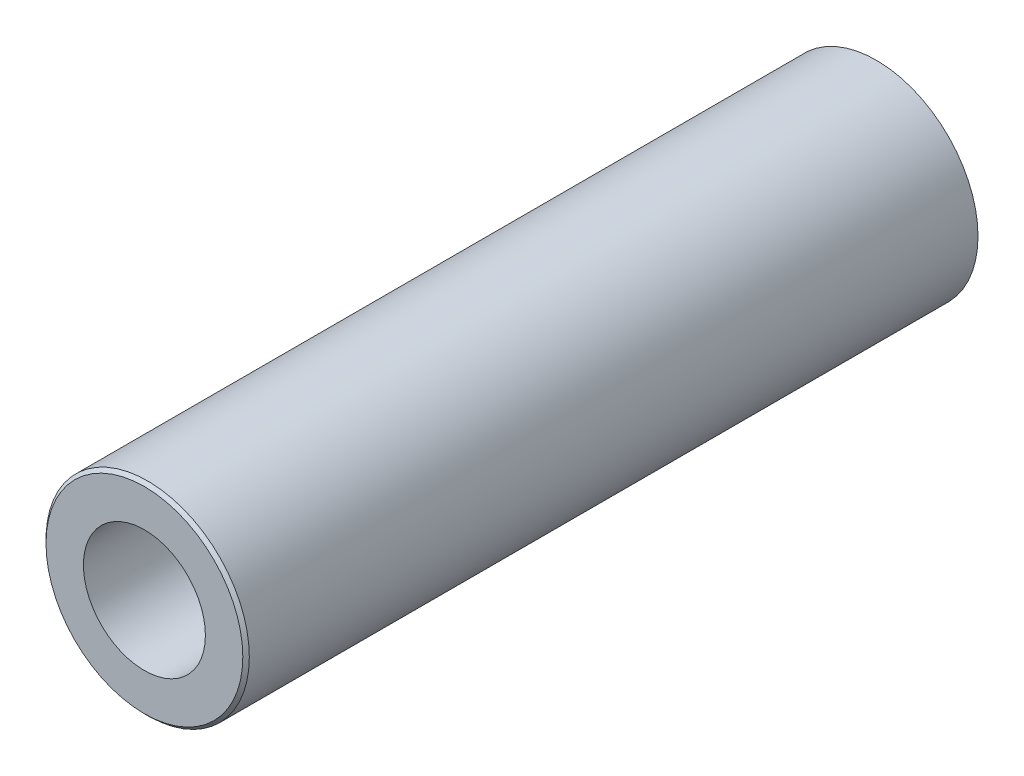
SolidWorks part; units mm, degrees
material "AISI 4130 Steel, annealed at 865C"
ref_plane "Front" through (0, 0, 0) normal (0, 0, 1) x (1, 0, 0)
ref_plane "Top" through (0, 0, 0) normal (0, 1, 0) x (1, 0, 0)
ref_plane "Right" through (0, 0, 0) normal (1, 0, 0) x (0, 0, -1)
sketch "Sketch1" plane through (0, 0, 0) normal (0, 0, 1) x (1, 0, 0)
  circle A0 centre (0, 0) radius 7.9375
  dimension "D1" = 15.875
extrude "Boss-Extrude1" add sketch "Sketch1" along normal blind 57.15
chamfer "Chamfer1" distance 0.254 angle 45 1 edges at (7.9375, 0, 57.15)
sketch "Sketch2" plane through (0, 0, 0) normal (0, 0, -1) x (-1, 0, 0)
  circle A0 centre (0, 0) radius 6.4643
  circle A1 centre (0, 0) radius 7.9375 construction
  dimension "D1" = 1.4732
sketch "Sketch4" [suppressed] plane through (0, 0, 19.05) normal (0, 0, 1) x (1, 0, 0)
  line L1 (6.4158, 0) -> (3.2079, 5.5563)
  line L2 (3.2079, 5.5563) -> (-3.2079, 5.5563)
  line L3 (-3.2079, 5.5563) -> (-6.4158, 0)
  line L4 (-6.4158, 0) -> (-3.2079, -5.5563)
  line L5 (-3.2079, -5.5563) -> (3.2079, -5.5563)
  line L6 (3.2079, -5.5563) -> (6.4158, 0)
  circle A0 centre (0, 0) radius 5.5562 construction
  circle A1 centre (0, 0) radius 6.35 construction
  circle A2 centre (0, 0) radius 6.35
  dimension "D1" = 11.1125
extrude "Cut-Extrude3" [suppressed] cut sketch "Sketch4" against normal blind 5.5562
hole_wizard "Tap Drill for 3/8-24 Tap1" [suppressed] positions "Sketch5" profile "Sketch6" hole size "3/8-24" standard "ANSI Inch"
sketch "Sketch5" plane through (0, 0, 15.875) normal (0, 0, 1) x (1, 0, 0)
  point P0 (0, 0)
sketch "Sketch6" plane through (0, 0, 15.875) normal (1, 0, 0) x (0, -1, 0)
  line L0 (0, 0) -> (0, 15.875)
  line L1 (0, 15.875) -> (4.2164, 15.875)
  line L2 (4.2164, 15.875) -> (4.2164, 0)
  line L5 (4.2164, 0) -> (0, 0)
  line L11 (0, -6.35) -> (0, 107.95) construction
  dimension "Thru Hole Dia." = 8.4328
  dimension "Thru Hole Depth" = 15.875
hole_wizard "5/16 (0.3125) Dowel Hole1" positions "Sketch7" profile "Sketch8" hole size "5/16" standard "ANSI Inch" end condition through all
sketch "Sketch7" plane through (0, 0, 57.15) normal (0, 0, 1) x (1, 0, 0)
  point P0 (0, 0)
sketch "Sketch8" plane through (0, 0, 57.15) normal (1, 0, 0) x (0, -1, 0)
  line L0 (0, 0) -> (0, 57.15)
  line L1 (0, 57.15) -> (4.7625, 57.15)
  line L2 (4.7625, 57.15) -> (4.7625, 0)
  line L5 (4.7625, 0) -> (0, 0)
  line L11 (0, -6.35) -> (0, 107.95) construction
  dimension "Thru Hole Dia." = 9.525
  dimension "Thru Hole Depth" = 57.15
hole_wizard "Tap Drill for 1/4-28 Tap1" [suppressed] positions "Sketch9" profile "Sketch10" hole size "1/4-28" standard "ANSI Inch"
sketch "Sketch9" plane through (0, 0, 19.05) normal (0, 0, 1) x (1, 0, 0)
  point P0 (0, 0)
sketch "Sketch10" plane through (0, 0, 19.05) normal (1, 0, 0) x (0, -1, 0)
  line L0 (0, 0) -> (0, 19.05)
  line L1 (0, 19.05) -> (2.7051, 19.05)
  line L2 (2.7051, 19.05) -> (2.7051, 0)
  line L5 (2.7051, 0) -> (0, 0)
  line L11 (0, -6.35) -> (0, 107.95) construction
  dimension "Thru Hole Dia." = 5.4102
  dimension "Thru Hole Depth" = 19.05
equation "\"Tube Radius\"= 5 / 16in"
equation "\"Wall Thickness\"= 0.058"
equation "\"D1@Sketch1\"= 2 * \"Tube Radius\""
equation "\"D1@Sketch2\" = \"Wall Thickness\""
